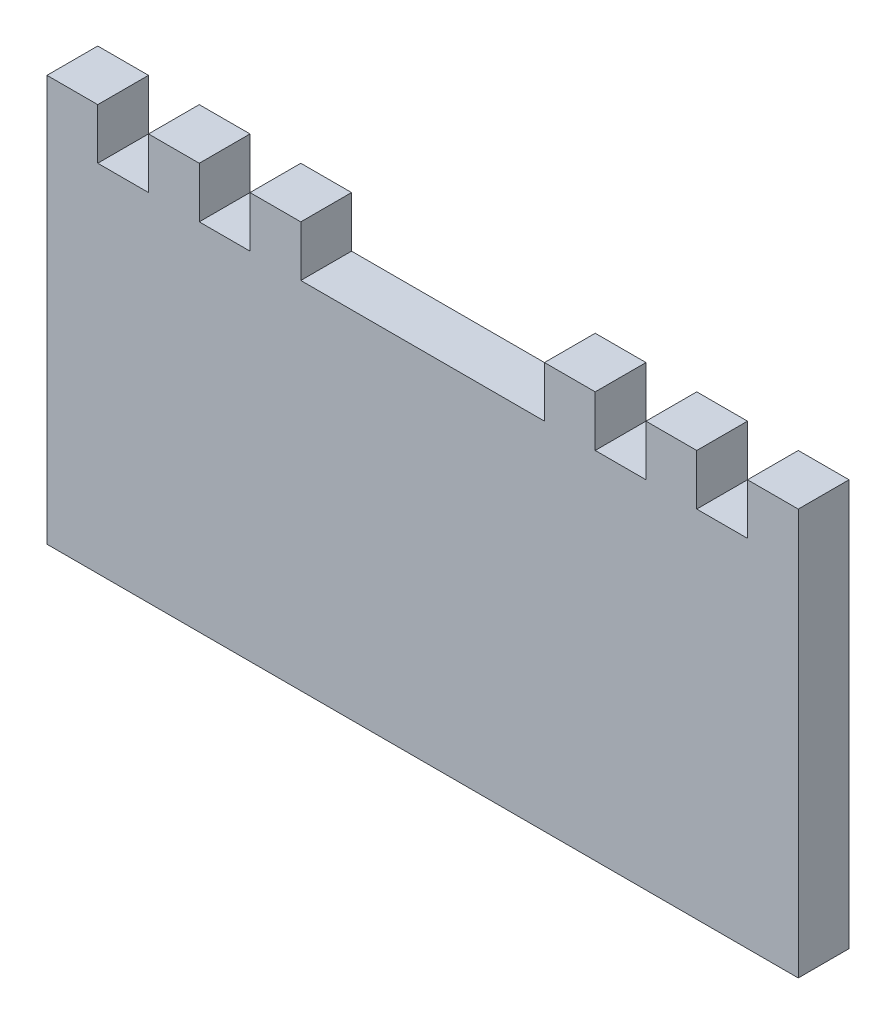
SolidWorks part; units mm, degrees
ref_plane "Plan de face" through (0, 0, 0) normal (0, 0, 1) x (1, 0, 0)
ref_plane "Plan de dessus" through (0, 0, 0) normal (0, 1, 0) x (1, 0, 0)
ref_plane "Plan de droite" through (0, 0, 0) normal (1, 0, 0) x (0, 0, -1)
sketch "Esquisse1" plane through (0, 0, 0) normal (0, 0, 1) x (1, 0, 0)
  line L0 (-43.1928, -9.5813) -> (-67.1928, -9.5813)
  line L14 (-18.1928, -44.5813) -> (-92.1928, -44.5813)
  line L16 (-67.1928, -4.5813) -> (-72.1928, -4.5813)
  line L17 (-82.1928, -4.5813) -> (-77.1928, -4.5813)
  line L33 (-43.1928, -4.5813) -> (-43.1928, -9.5813)
  line L35 (-38.1928, -4.5813) -> (-38.1928, -9.5813)
  line L36 (-38.1928, -9.5813) -> (-33.1928, -9.5813)
  line L37 (-33.1928, -4.5813) -> (-33.1928, -9.5813)
  line L39 (-28.1928, -4.5813) -> (-28.1928, -9.5813)
  line L40 (-28.1928, -9.5813) -> (-23.1928, -9.5813)
  line L41 (-23.1928, -4.5813) -> (-23.1928, -9.5813)
  line L42 (-92.1928, -4.5813) -> (-87.1928, -4.5813)
  line L43 (-92.1928, -44.5813) -> (-92.1928, -4.5813)
  line L44 (-18.1928, -44.5813) -> (-18.1928, -4.5813)
  line L45 (-18.1928, -4.5813) -> (-23.1928, -4.5813)
  line L46 (-28.1928, -4.5813) -> (-33.1928, -4.5813)
  line L47 (-87.1928, -4.5813) -> (-87.1928, -9.5813)
  line L48 (-82.1928, -9.5813) -> (-87.1928, -9.5813)
  line L49 (-82.1928, -4.5813) -> (-82.1928, -9.5813)
  line L50 (-77.1928, -4.5813) -> (-77.1928, -9.5813)
  line L51 (-72.1928, -9.5813) -> (-77.1928, -9.5813)
  line L52 (-43.1928, -4.5813) -> (-38.1928, -4.5813)
  line L53 (-72.1928, -4.5813) -> (-72.1928, -9.5813)
  line L54 (-67.1928, -4.5813) -> (-67.1928, -9.5813)
  dimension "D6" = 5
  dimension "D7" = 5
  dimension "D11" = 5
  dimension "D14" = 5
  dimension "D15" = 5
  dimension "D16" = 5
  dimension "D17" = 5
  dimension "D18" = 5
  dimension "D19" = 5
extrude "Boss.-Extru.1" add sketch "Esquisse1" along normal blind 5
